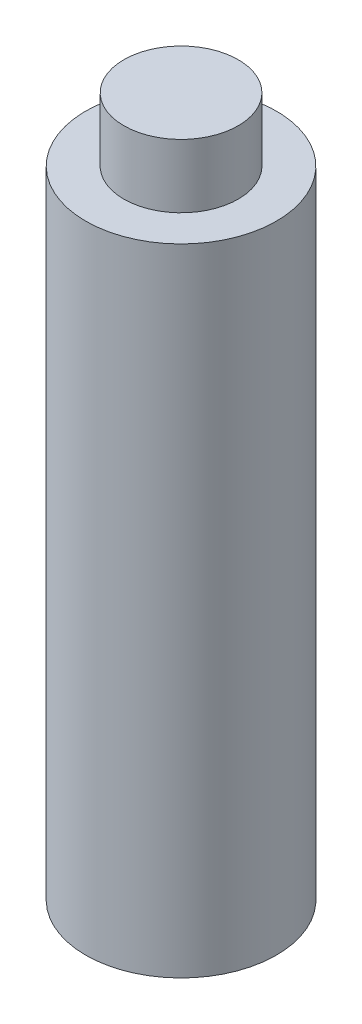
SolidWorks part; units mm, degrees
ref_plane "Front Plane" through (0, 0, 0) normal (0, 0, 1) x (1, 0, 0)
ref_plane "Top Plane" through (0, 0, 0) normal (0, 1, 0) x (1, 0, 0)
ref_plane "Right Plane" through (0, 0, 0) normal (1, 0, 0) x (0, 0, -1)
sketch "Sketch1" plane through (0, 0, 0) normal (0, 1, 0) x (1, 0, 0)
  circle A0 centre (0, 0) radius 7.5
  dimension "D1" = 15
extrude "Boss-Extrude1" add sketch "Sketch1" along normal blind 50
sketch "Sketch2" plane through (0, 50, 0) normal (0, 1, 0) x (1, 0, 0)
  circle A0 centre (0, 0) radius 4.5
  dimension "D1" = 9
extrude "Boss-Extrude2" add sketch "Sketch2" along normal blind 5
